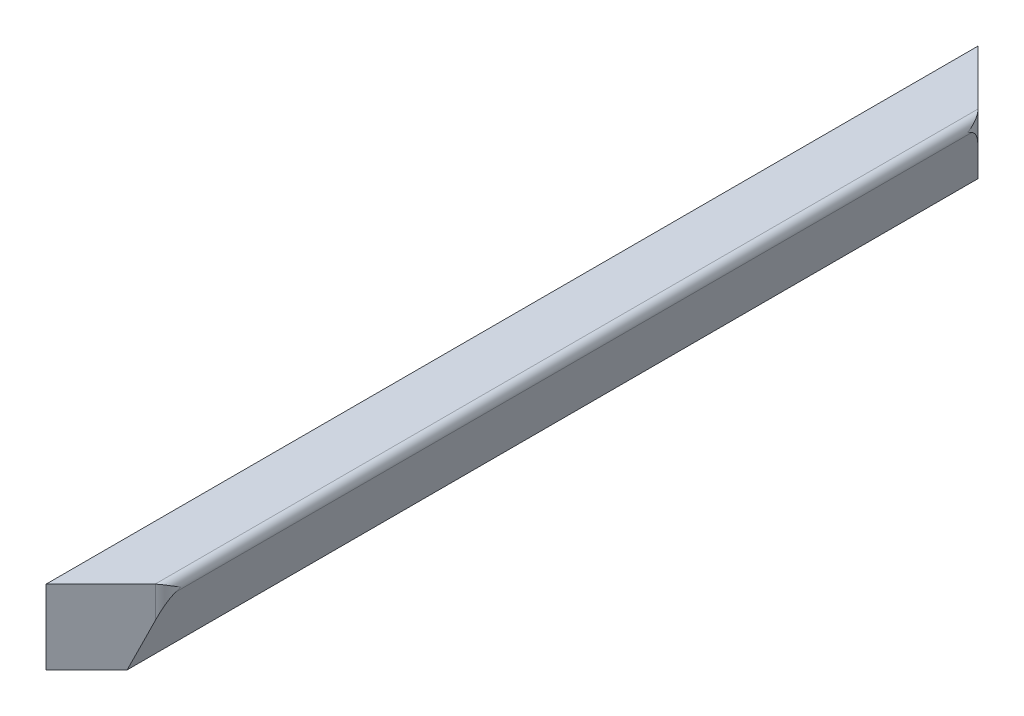
SolidWorks part; units mm, degrees
ref_plane "Alzado" through (0, 0, 0) normal (0, 0, 1) x (1, 0, 0)
ref_plane "Planta" through (0, 0, 0) normal (0, 1, 0) x (1, 0, 0)
ref_plane "Vista lateral" through (0, 0, 0) normal (1, 0, 0) x (0, 0, -1)
sketch "Croquis1" plane through (0, 0, 0) normal (0, 0, 1) x (1, 0, 0)
  line L0 (-24.95, 2.07) -> (-24.95, 5)
  line L1 (-24.95, 5) -> (-22.8, 5)
  line L3 (-24.95, 4.7) -> (-22.5, 4.7) construction
  line L4 (-22.515, 4.6062) -> (-23.35, 2.07)
  line L5 (-23.35, 2.07) -> (-24.95, 2.07)
  arc A0 (-22.8, 5) -> (-22.515, 4.6062) centre (-22.8, 4.7) cw
  dimension "D2" = 0.3
  dimension "D1" = 2.45
  dimension "D3" = 2.93
  dimension "D4" = 0.85
extrude "Saliente-Extruir1" add sketch "Croquis1" against normal blind 36.7642
sketch "Croquis3" plane through (0, 5, 0) normal (0, 1, 0) x (1, 0, 0)
  line L0 (-24.95, 36.7642) -> (-22.7929, 34.6071)
  line L1 (-22.5, 0) -> (-22.5, 36.7642) construction
  line L2 (-22.5, 0) -> (-22.5, 36.7642) construction
  line L3 (-22.5, 33.9) -> (-22.5, 2.8642)
  line L4 (-22.7929, 2.1571) -> (-24.95, 0)
  line L5 (-24.95, 0) -> (-24.95, -1.3539)
  line L6 (-24.95, -1.3539) -> (-20.6762, -1.3539)
  line L7 (-20.6762, -1.3539) -> (-20.6762, 38.5719)
  line L8 (-20.6762, 38.5719) -> (-24.95, 38.5719)
  line L9 (-24.95, 38.5719) -> (-24.95, 36.7642)
  line L10 (-24.95, 36.7642) -> (-24.95, 0) construction
  arc A0 (-22.7929, 2.1571) -> (-22.5, 2.8642) centre (-23.5, 2.8642) ccw
  arc A1 (-22.5, 33.9) -> (-22.7929, 34.6071) centre (-23.5, 33.9) ccw
  point P16 (-22.5, 2.45)
  point P19 (-22.5, 34.3142)
  dimension "D3" = 1
  dimension "D1" = 45
  dimension "D2" = 45
extrude "Cortar-Extruir1" cut sketch "Croquis3" against normal up to surface (2.93 mm away) up to face at (-24.15, 2.07, -18.3821)
